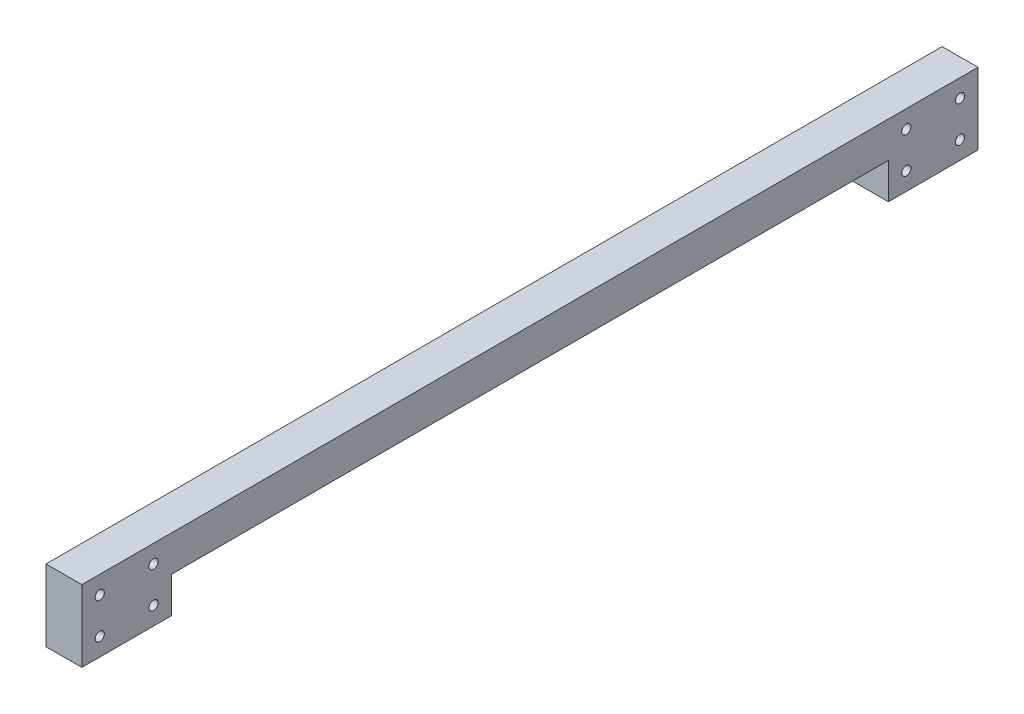
SolidWorks part; units mm, degrees
ref_plane "Front" through (0, 0, 0) normal (0, 0, 1) x (1, 0, 0)
ref_plane "Top" through (0, 0, 0) normal (0, 1, 0) x (1, 0, 0)
ref_plane "Right" through (0, 0, 0) normal (1, 0, 0) x (0, 0, -1)
sketch "草图1" plane through (0, 0, 0) normal (0, 0, 1) x (1, 0, 0)
  line L1 (-10, 10) -> (10, 10)
  line L2 (-10, 10) -> (-10, -10)
  line L3 (-10, -10) -> (10, -10)
  line L4 (10, 10) -> (10, -10)
  line L5 (-10, 10) -> (10, -10) construction
  line L6 (-10, -10) -> (10, 10) construction
  point P0 (0, 0)
  dimension "D1" = 20
  dimension "D2" = 20
extrude "凸台-拉伸2" add sketch "草图1" along normal blind 500
sketch "草图2" plane through (10, 0, 0) normal (1, 0, 0) x (0, 0, -1)
  line L0 (0, -10) -> (0, 10) construction
  circle A0 centre (-10, 0) radius 2.55
  circle A1 centre (-40, 0) radius 2.55
  dimension "D1" = 5.1
  dimension "D3" = 5.1
  dimension "D4" = 30
  dimension "D2" = 10
extrude "切除-拉伸1" cut sketch "草图2" against normal up to next
sketch "草图3" plane through (0, -10, 0) normal (0, -1, 0) x (1, 0, 0)
  line L0 (10, 500) -> (10, 0) construction
  line L1 (-10, 0) -> (10, 0)
  line L2 (-10, 0) -> (-10, 50)
  line L3 (-10, 50) -> (10, 50)
  line L4 (10, 0) -> (10, 50)
extrude "凸台-拉伸3" add sketch "草图3" along normal blind 20
sketch "草图4" plane through (10, 0, 0) normal (1, 0, 0) x (0, 0, -1)
  line L0 (-50, -30) -> (-50, -10) construction
  line L1 (0, -30) -> (0, 10) construction
  circle A0 centre (-40, -20) radius 2.55
  circle A1 centre (-10, -20) radius 2.55
  dimension "D1" = 5.1
  dimension "D2" = 5.1
  dimension "D3" = 10
  dimension "D4" = 10
extrude "切除-拉伸2" cut sketch "草图4" against normal blind 20
sketch "草图5" plane through (0, 0, 500) normal (0, 0, 1) x (1, 0, 0)
  line L1 (-10, -10) -> (10, -10)
  line L2 (-10, -10) -> (-10, 10)
  line L3 (-10, 10) -> (10, 10)
  line L4 (10, -10) -> (10, 10)
extrude "切除-拉伸3" cut sketch "草图5" against normal blind 250
mirror "镜向2" about plane through (0, 0, 250) normal (0, 0, -1) of "凸台-拉伸3", "凸台-拉伸2"
sketch "草图6" plane through (10, 0, 0) normal (1, 0, 0) x (0, 0, -1)
  line L0 (-500, -30) -> (-500, 10) construction
  circle A0 centre (-490, 0) radius 2.55
  circle A1 centre (-460, 0) radius 2.55
  circle A2 centre (-460, -20) radius 2.55
  circle A3 centre (-490, -20) radius 2.55
  circle A4 centre (-10, 0) radius 2.55
  circle A5 centre (-40, 0) radius 2.55
  dimension "D1" = 5.1
  dimension "D2" = 5.1
  dimension "D3" = 5.1
  dimension "D4" = 5.1
  dimension "D9" = 5.1
  dimension "D10" = 5.1
  dimension "D5" = 10
  dimension "D6" = 30
  dimension "D7" = 10
  dimension "D8" = 30
extrude "切除-拉伸4" cut sketch "草图6" against normal up to next
